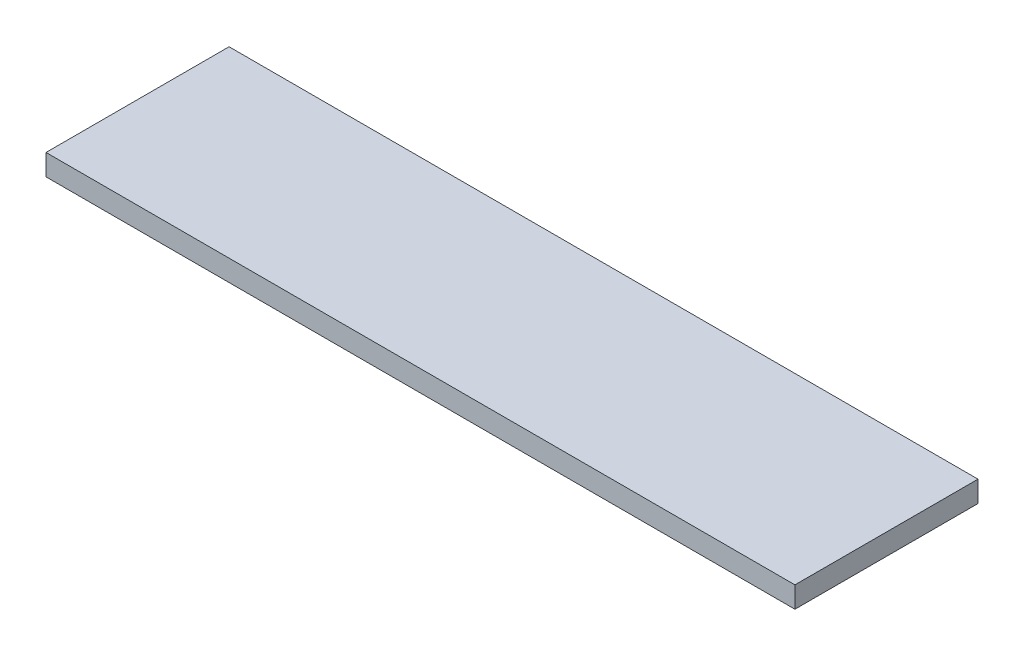
SolidWorks part; units mm, degrees
ref_plane "Front Plane" through (0, 0, 0) normal (0, 0, 1) x (1, 0, 0)
ref_plane "Top Plane" through (0, 0, 0) normal (0, 1, 0) x (1, 0, 0)
ref_plane "Right Plane" through (0, 0, 0) normal (1, 0, 0) x (0, 0, -1)
sketch "Sketch1" plane through (0, 0, 0) normal (0, 1, 0) x (1, 0, 0)
  line L1 (-45, -11) -> (45, -11)
  line L2 (-45, -11) -> (-45, 11)
  line L3 (-45, 11) -> (45, 11)
  line L4 (45, -11) -> (45, 11)
  line L5 (-45, -11) -> (45, 11) construction
  line L6 (-45, 11) -> (45, -11) construction
  point P0 (0, 0)
  dimension "D1" = 90
  dimension "D2" = 22
extrude "Boss-Extrude1" add sketch "Sketch1" along normal blind 2.54
